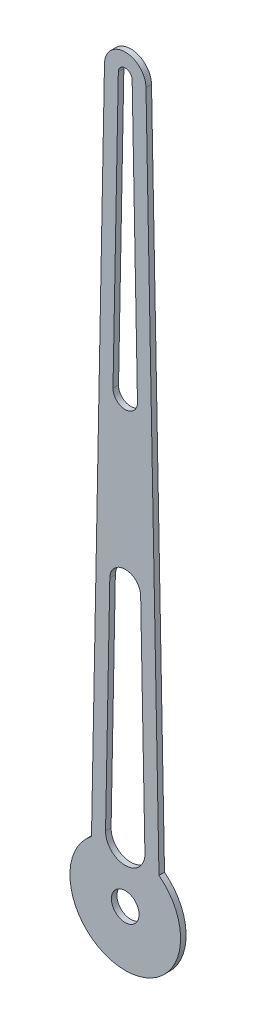
SolidWorks part; units mm, degrees
material "PW110:Mi:0:2:C1:0:1:2:Re:26:"
ref_plane "Front" through (0, 0, 0) normal (0, 0, 1) x (1, 0, 0)
ref_plane "Top" through (0, 0, 0) normal (0, 1, 0) x (1, 0, 0)
ref_plane "Right" through (0, 0, 0) normal (1, 0, 0) x (0, 0, -1)
sketch "Sketch1" plane through (0, 0, 0) normal (0, 0, 1) x (1, 0, 0)
  line L0 (-19.6851, 0) -> (20.2961, 0) construction
  line L1 (0, 17.3189) -> (0, -16.8635) construction
  circle A0 centre (10, 0) radius 1.75 construction
  circle A1 centre (-7.5, 0) radius 4 construction
  circle A2 centre (0, 7.5) radius 4 construction
  circle A3 centre (0, -7.5) radius 4 construction
  point P12 (0, 0)
  dimension "D1" = 8
  dimension "D2" = 8
  dimension "D3" = 8
  dimension "D4" = 3.5
  dimension "D5" = 10
  dimension "D6" = 7.5
  dimension "D7" = 7.5
  dimension "D8" = 7.5
sketch "Sketch2" plane through (0, 0, 0) normal (0, 0, 1) x (1, 0, 0)
  line L0 (0, 17.3189) -> (0, -16.8635) construction
  line L1 (0.3749, 13.0072) -> (0.6099, 0.7925)
  line L2 (-0.3749, 13.0072) -> (-0.6099, 0.7925)
  line L3 (0.125, 13.0024) -> (0.2211, 8.0043)
  line L4 (-0.125, 13.0024) -> (-0.2211, 8.0043)
  line L5 (-0.2788, 5.0054) -> (-0.3557, 1.0068)
  line L6 (0.2788, 5.0054) -> (0.3557, 1.0068)
  arc A0 (-0.3557, 1.0068) -> (0.3557, 1.0068) centre (0, 1) ccw
  arc A1 (0.3749, 13.0072) -> (-0.3749, 13.0072) centre (0, 13) ccw
  arc A2 (-0.6099, 0.7925) -> (0.6099, 0.7925) centre (0, 0) ccw
  circle A3 centre (0, 0) radius 0.25
  arc A4 (0.125, 13.0024) -> (-0.125, 13.0024) centre (0, 13) ccw
  arc A5 (0.2788, 5.0054) -> (-0.2788, 5.0054) centre (0, 5) ccw
  arc A6 (-0.2211, 8.0043) -> (0.2211, 8.0043) centre (0, 8) ccw
  dimension "D1" = 4
  dimension "D2" = 0.75
  dimension "D4" = 0.25
  dimension "D5" = 5
  dimension "D3" = 13
  dimension "D6" = 5
extrude "Base-Extrude" add sketch "Sketch2" along normal blind 0.1
